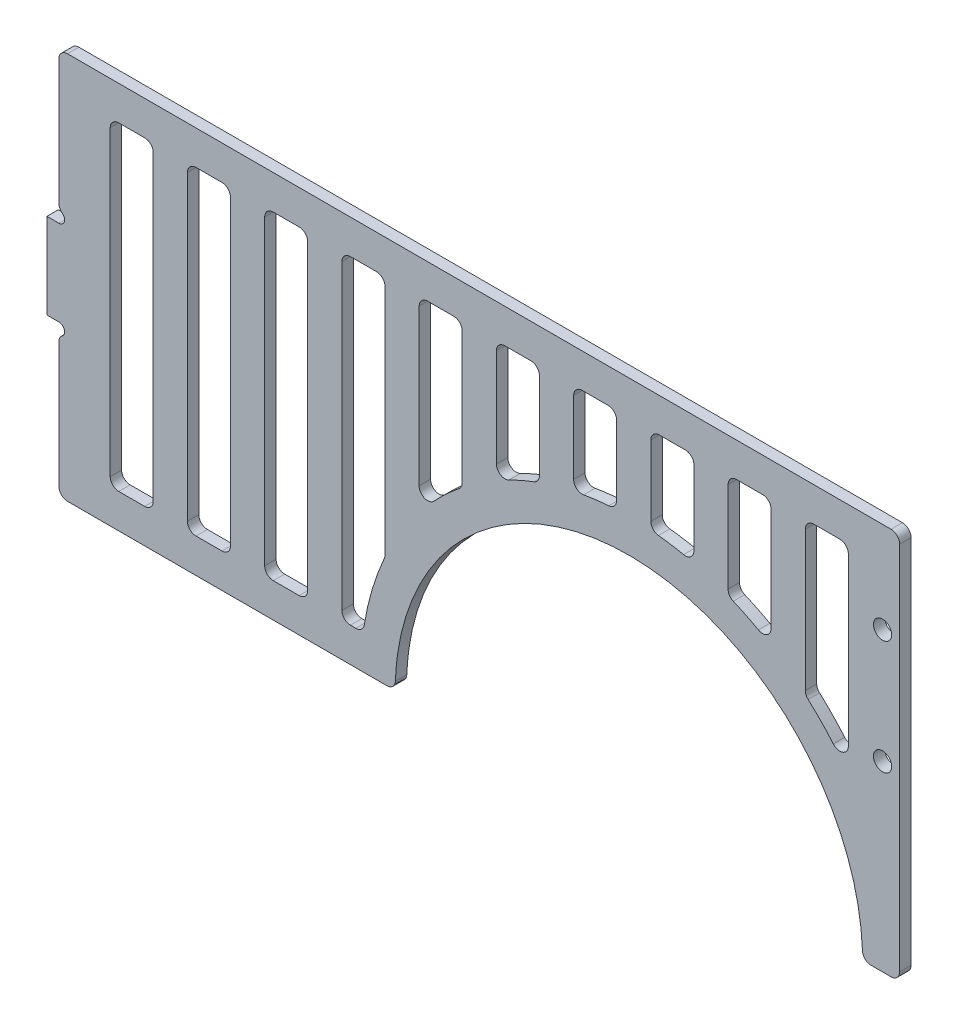
SolidWorks part; units mm, degrees
material "Thornel Mat VMA"
ref_plane "前视基准面" through (0, 0, 0) normal (0, 0, 1) x (1, 0, 0)
ref_plane "上视基准面" through (0, 0, 0) normal (0, 1, 0) x (1, 0, 0)
ref_plane "右视基准面" through (0, 0, 0) normal (1, 0, 0) x (0, 0, -1)
other "Configuration Table"
sketch "草图1" plane through (0, 0, 0) normal (0, 0, 1) x (1, 0, 0)
  line L1 (-73.75, 34) -> (73.75, 34)
  line L2 (-73.75, 34) -> (-73.75, -34)
  line L3 (-73.75, -34) -> (73.75, -34)
  line L4 (73.75, 34) -> (73.75, -34)
  line L5 (-73.75, 34) -> (73.75, -34) construction
  line L6 (-73.75, -34) -> (73.75, 34) construction
  point P0 (0, 0)
  dimension "D1" = 68
  dimension "D2" = 147.5
extrude "凸台-拉伸1" add sketch "草图1" along normal blind 2
sketch "草图2" plane through (0, 0, 2) normal (0, 0, 1) x (1, 0, 0)
  line L0 (-73.75, 34) -> (-73.75, -34) construction
  line L1 (-73.75, -7.5) -> (-75.85, -7.5)
  line L2 (-73.75, -7.5) -> (-73.75, 7.5)
  line L3 (-73.75, 7.5) -> (-75.85, 7.5)
  line L4 (-75.85, -7.5) -> (-75.85, 7.5)
  point P6 (-73.75, 0)
  dimension "D1" = 2.1
  dimension "D2" = 15
extrude "凸台-拉伸2" add sketch "草图2" against normal blind 2
sketch "草图3" plane through (0, 0, 2) normal (0, 0, 1) x (1, 0, 0)
  line L0 (-73.75, 34) -> (-73.75, 7.5) construction
  line L1 (-73.75, -7.5) -> (-73.75, -34) construction
  line L2 (-75.85, -7.5) -> (-73.75, -7.5) construction
  line L3 (-73.75, 7.5) -> (-75.85, 7.5) construction
  circle A0 centre (-73.75, 8.5) radius 1
  circle A1 centre (-73.75, -8.5) radius 1
  dimension "D1" = 2
extrude "切除-拉伸1" cut sketch "草图3" against normal blind 10
sketch "草图4" plane through (0, -1.239, -15.1845) normal (0, -0.0813, -0.9967) x (-1, 0, 0)
  circle A1 centre (-26.25, -34.1126) radius 41
  dimension "D1" = 82
  dimension "D2" = 34.1126
  dimension "D3" = 26.25
extrude "切除-拉伸2" cut sketch "草图4" against normal through all
sketch "草图5" plane through (0, 0, 2) normal (0, 0, 1) x (1, 0, 0)
  line L0 (67.75, -28) -> (-67.75, -28)
  line L1 (73.75, -34) -> (-73.75, -34)
  line L2 (73.75, -34) -> (73.75, 34)
  line L3 (73.75, 34) -> (-73.75, 34)
  line L4 (-73.75, -34) -> (-73.75, 34)
  line L5 (-67.75, -28) -> (-67.75, 28)
  line L6 (67.75, 28) -> (-67.75, 28)
  line L7 (67.75, -28) -> (67.75, 28)
  line L8 (54.2, -28) -> (54.2, 28)
  line L9 (40.65, -28) -> (40.65, 28)
  line L10 (27.1, -28) -> (27.1, 28)
  line L11 (13.55, -28) -> (13.55, 28)
  line L12 (0, -28) -> (0, 28)
  line L13 (-13.55, -28) -> (-13.55, 28)
  line L14 (-27.1, -28) -> (-27.1, 28)
  line L15 (-40.65, -28) -> (-40.65, 28)
  line L16 (-54.2, -28) -> (-54.2, 28)
  line L17 (-51.2, -28) -> (-51.2, 28)
  line L18 (-37.65, -28) -> (-37.65, 28)
  line L19 (-24.1, -28) -> (-24.1, 28)
  line L20 (-10.55, -28) -> (-10.55, 28)
  line L21 (3, -28) -> (3, 28)
  line L22 (16.55, -28) -> (16.55, 28)
  line L23 (30.1, -28) -> (30.1, 28)
  line L24 (43.65, -28) -> (43.65, 28)
  line L25 (57.2, -28) -> (57.2, 28)
  line L26 (-57.2, -28) -> (-57.2, 28)
  line L27 (-43.65, -28) -> (-43.65, 28)
  line L28 (-30.1, -28) -> (-30.1, 28)
  line L29 (-16.55, -28) -> (-16.55, 28)
  line L30 (-3, -28) -> (-3, 28)
  line L31 (10.55, -28) -> (10.55, 28)
  line L32 (24.1, -28) -> (24.1, 28)
  line L33 (37.65, -28) -> (37.65, 28)
  line L34 (51.2, -28) -> (51.2, 28)
  line L35 (-70.75, -28) -> (-70.75, 28)
  line L36 (64.75, -28) -> (64.75, 28)
  line L37 (-64.75, -28) -> (-64.75, 28)
  line L38 (70.75, -28) -> (70.75, 28)
  circle A0 centre (26.25, -34.0628) radius 41
  circle A1 centre (26.25, -34.0628) radius 47
  ellipse E0 centre (26.25, -34.0628) end of major axis (26.25, 7.0735) minor radius 41 (67.25, -34) -> (-14.75, -34) ccw construction
  dimension "D3" = 10
  dimension "D4" = 13.55
  dimension "D1" = 6
  dimension "D2" = 6
  dimension "D5" = 3
  dimension "D6" = 3
  dimension "D7" = 3
  dimension "D8" = 3
extrude "切除-拉伸3" cut sketch "草图5" against normal blind 10 contours A1 L36 L6 L25 | A1 L34 L6 L24 | A1 L33 L6 L23 | A1 L32 L6 L22 | A1 L31 L6 L21 | A1 L30 L6 L20 | A1 L29 L6 L19 L0 | L0 L28 L6 L18 | L0 L27 L6 L17 | L37 L0 L26 L6
fillet "圆角1" radius 1.5 49 edges at (-14.7497, -34, 1) (67.2497, -34, 1) (-73.75, -34, 1) (-73.75, -9.5, 1) (-73.75, 9.5, 1) (-73.75, 34, 1) (73.75, 34, 1) (73.75, -34, 1) (57.2, 1.3081, 1) (57.2, 28, 1) (64.75, 28, 1) (30.1, 12.7793, 1) (30.1, 28, 1) (37.65, 28, 1) (37.65, 11.5337, 1) (3, 6.7837, 1) (3, 28, 1) (10.55, 28, 1) (10.55, 10.2374, 1) (-20.3573, -28, 1) (-24.1, -28, 1) (-24.1, 28, 1) (-16.55, 28, 1) (-16.55, -14.6422, 1) (-51.2, -28, 1) (-51.2, 28, 1) (-43.65, 28, 1) (-43.65, -28, 1) (-64.75, 28, 1) (-57.2, 28, 1) (-57.2, -28, 1) (-64.75, -28, 1) (-37.65, -28, 1) (-37.65, 28, 1) (-30.1, 28, 1) (-30.1, -28, 1) (-10.55, -4.8265, 1) (-10.55, 28, 1) (-3, 28, 1) (-3, 2.7263, 1) (16.55, 11.9254, 1) (16.55, 28, 1) (24.1, 28, 1) (24.1, 12.888, 1) (43.65, 9.5977, 1) (43.65, 28, 1) (51.2, 28, 1) (51.2, 5.7681, 1) (64.75, -7.1045, 1)
sketch "草图6" plane through (0, 0, 2) normal (0, 0, 1) x (1, 0, 0)
  line L0 (70.75, 18) -> (70.75, -2) construction
  line L1 (72.25, 34) -> (-72.25, 34) construction
  line L2 (73.75, -32.5) -> (73.75, 32.5) construction
  circle A0 centre (70.75, -2) radius 1.6
  circle A1 centre (70.75, 18) radius 1.6
  point P8 (70.75, 6.4375)
  dimension "D3" = 3.2
  dimension "D1" = 16
  dimension "D2" = 3
  dimension "D4" = 20
extrude "切除-拉伸4" cut sketch "草图6" against normal through all
